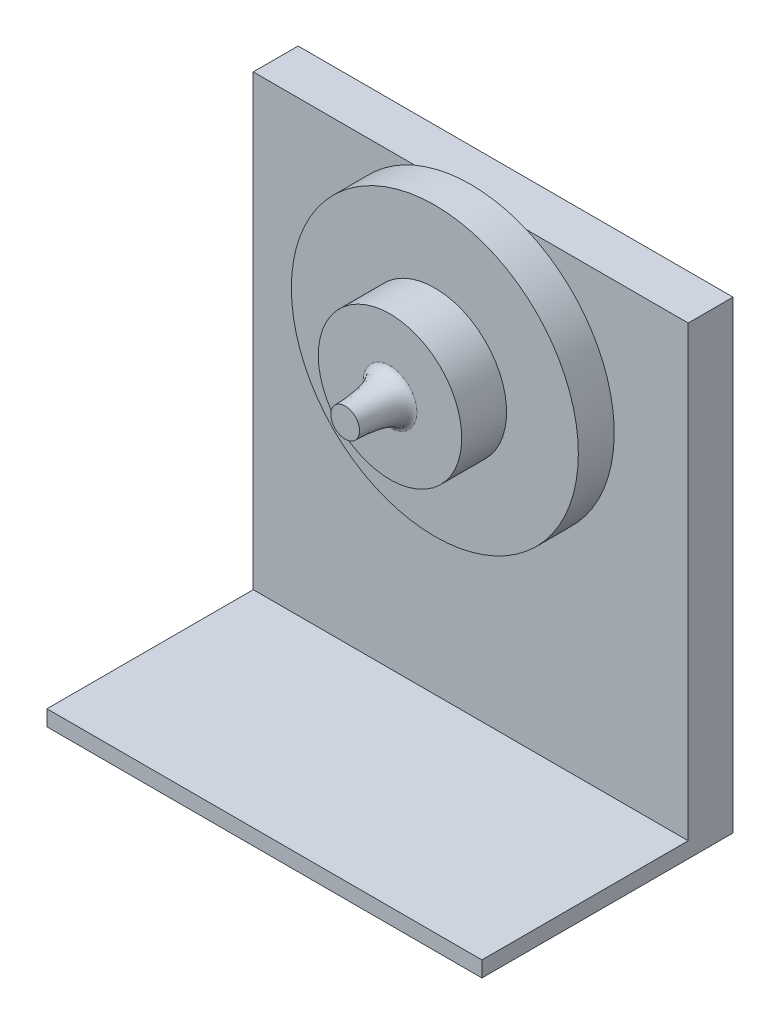
SolidWorks part; units mm, degrees
ref_plane "Front Plane" through (0, 0, 0) normal (0, 0, 1) x (1, 0, 0)
ref_plane "Top Plane" through (0, 0, 0) normal (0, 1, 0) x (1, 0, 0)
ref_plane "Right Plane" through (0, 0, 0) normal (1, 0, 0) x (0, 0, -1)
sketch "Sketch1" plane through (0, 0, 0) normal (0, 0, 1) x (1, 0, 0)
  line L1 (-242.5, 0) -> (242.5, 0)
  line L2 (-242.5, 0) -> (-242.5, 500)
  line L3 (-242.5, 500) -> (242.5, 500)
  line L4 (242.5, 0) -> (242.5, 500)
  point P4 (0, 0)
  dimension "D1" = 500
  dimension "D2" = 485
extrude "Boss-Extrude1" add sketch "Sketch1" against normal blind 50
sketch "Sketch2" plane through (0, 0, 0) normal (0, 1, 0) x (1, 0, 0)
  line L0 (242.5, 50) -> (-242.5, 50) construction
  line L1 (-242.5, 50) -> (242.5, 50)
  line L2 (-242.5, 50) -> (-242.5, -230)
  line L3 (-242.5, -230) -> (242.5, -230)
  line L4 (242.5, 50) -> (242.5, -230)
  line L5 (242.5, 0) -> (-242.5, 0) construction
  dimension "D1" = 230
extrude "Boss-Extrude2" add sketch "Sketch2" against normal blind 17.5
ref_plane "Plane2" through (0, 352.6, 0) normal (0, 1, 0) x (1, 0, 0)
sketch "Sketch6" plane through (0, 352.6, 0) normal (0, 1, 0) x (1, 0, 0)
  line L0 (0, 0) -> (160, 0)
  line L1 (242.5, 0) -> (-242.5, 0) construction
  line L2 (160, 0) -> (160, -40)
  line L3 (160, -40) -> (80, -40)
  line L4 (80, -40) -> (80, -90)
  line L5 (80, -90) -> (30, -90)
  line L6 (0, 0) -> (0, -140)
  line L7 (-242.5, 0) -> (242.5, 0) construction
  line L8 (16, -95) -> (16, -268.471) construction
  line L9 (16, -193.3388) -> (16, -124.4635) construction
  line L10 (15.691, -140) -> (0, -140)
  line L11 (16, -140) -> (15.691, -140)
  spline S0 degree 3 poles (30, -90) (19.3054, -92.0133) (16, -123.8733) (16, -140) knots 0 0 0 0 1 1 1 1
  dimension "D1" = 160
  dimension "D2" = 80
  dimension "D3" = 50
  dimension "D4" = 40
  dimension "D5" = 16
  dimension "D6" = 30
  dimension "D7" = 50
revolve "Revolve1" add sketch "Sketch6" angle 360 about L6
